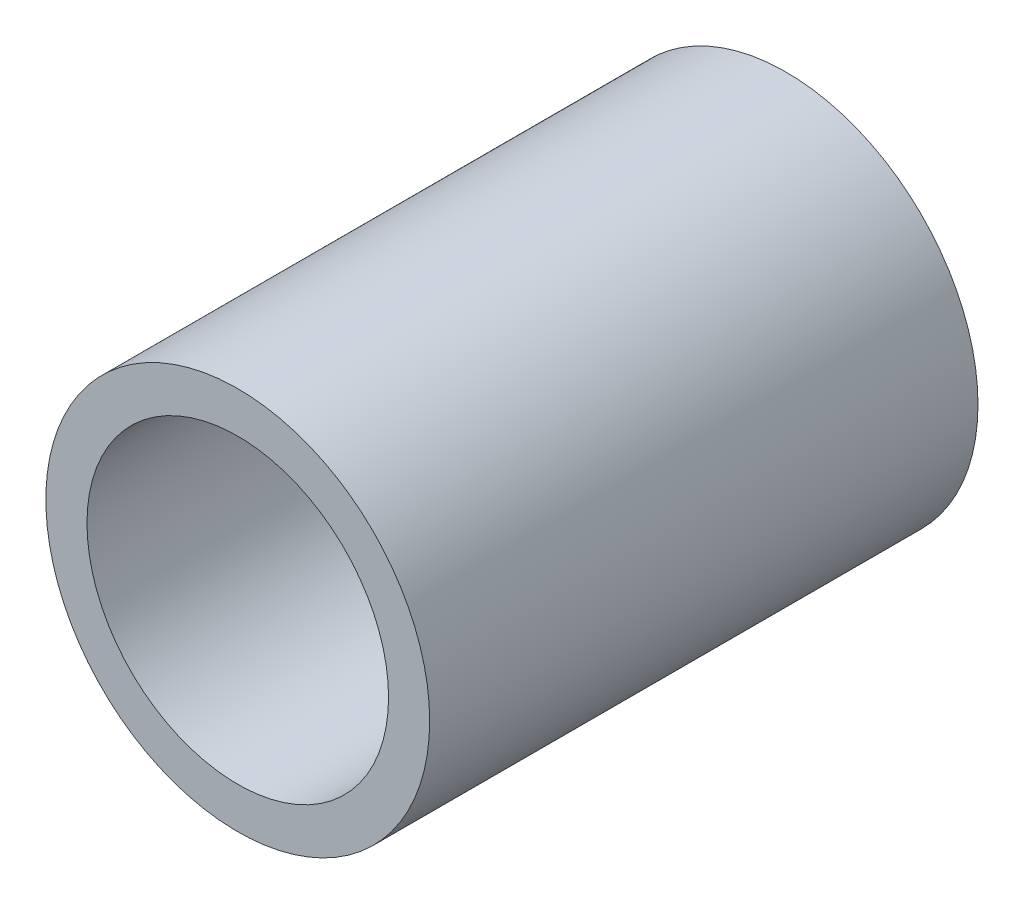
SolidWorks part; units mm, degrees
ref_plane "Plan de face" through (0, 0, 0) normal (0, 0, 1) x (1, 0, 0)
ref_plane "Plan de dessus" through (0, 0, 0) normal (0, 1, 0) x (1, 0, 0)
ref_plane "Plan de droite" through (0, 0, 0) normal (1, 0, 0) x (0, 0, -1)
sketch "Esquisse1" plane through (0, 0, 0) normal (0, 0, 1) x (1, 0, 0)
  circle A0 centre (0, 0) radius 28
extrude "Boss.-Extru.1" add sketch "Esquisse1" along normal blind 80
sketch "Esquisse2" plane through (0, 0, 80) normal (0, 0, 1) x (1, 0, 0)
  circle A0 centre (0, 0) radius 22
extrude "Enlèv. mat.-Extru.2" cut sketch "Esquisse2" against normal blind 100
